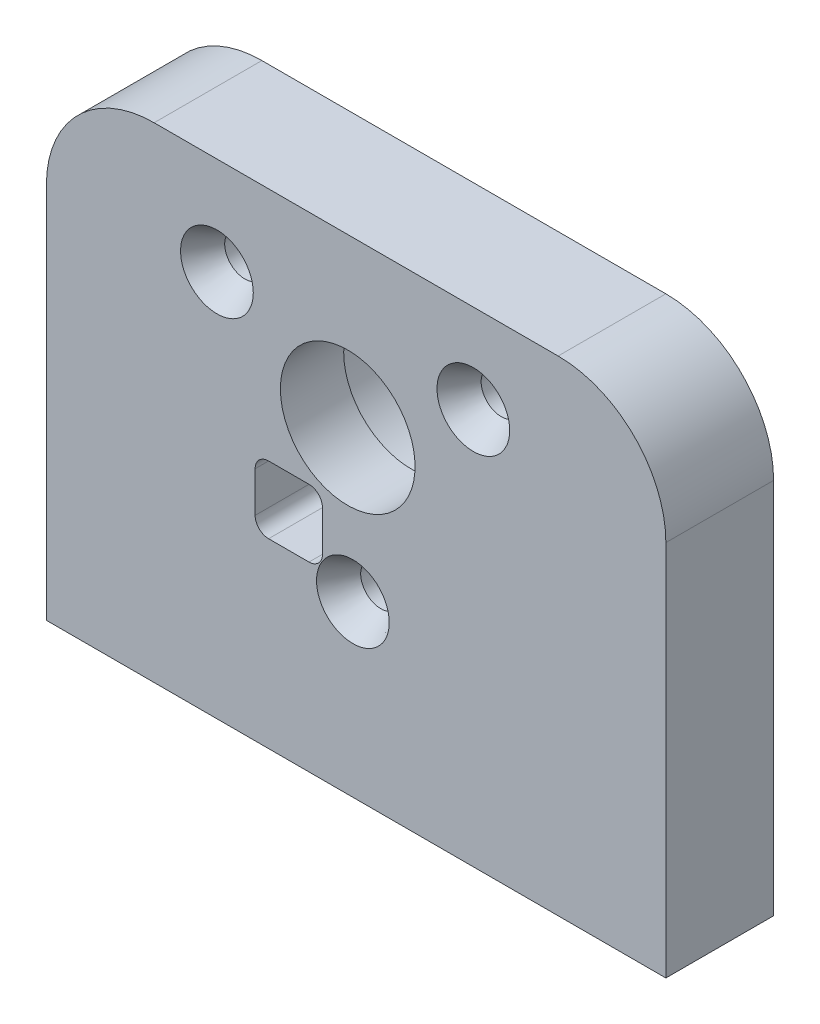
SolidWorks part; units mm, degrees
ref_plane "Front Plane" through (0, 0, 0) normal (0, 0, 1) x (1, 0, 0)
ref_plane "Top Plane" through (0, 0, 0) normal (0, 1, 0) x (1, 0, 0)
ref_plane "Right Plane" through (0, 0, 0) normal (1, 0, 0) x (0, 0, -1)
ref_plane "Plane1" through (0, 0, 4.5) normal (0, 0, 1) x (1, 0, 0)
sketch "Sketch1" plane through (0, 0, 4.5) normal (0, 0, 1) x (1, 0, 0)
  line L0 (-23, -18) -> (23, -18)
  line L1 (23, -18) -> (23, 18)
  line L2 (23, 18) -> (-23, 18)
  line L3 (-23, 18) -> (-23, -18)
extrude "Boss-Extrude1" add sketch "Sketch1" against normal blind 8
hole_wizard "M3x0.5 Tapped Hole1" positions "Sketch6" profile "Sketch5" tap size "M3x0.5" standard "ANSI Metric"
sketch "Sketch6" plane through (0, -18, 0) normal (0, -1, 0) x (-1, 0, 0)
  line L0 (23, -4.5) -> (-23, -4.5) construction
  point P0 (0, -0.5)
  dimension "D1" = 4
sketch "Sketch5" plane through (0, -18, 0.5) normal (1, 0, 0) x (0, 0, -1)
  line L0 (0, 0) -> (0, 8.2511)
  line L1 (0, 8.2511) -> (1.25, 7.5)
  line L2 (1.25, 7.5) -> (1.25, 0)
  line L5 (1.25, 0) -> (0, 0)
  line L10 (0, 8.2511) -> (-1.25, 7.5) construction
  line L11 (0, -6.35) -> (0, 107.95) construction
  dimension "Tap Drill Dia." = 2.5
  dimension "Tap Drill Depth" = 7.5
  dimension "Drill Angle" = 118
hole_wizard "M3x0.5 Tapped Hole2" positions "Sketch8" profile "Sketch7" tap size "M3x0.5" standard "ANSI Metric"
sketch "Sketch8" plane through (0, -18, 0) normal (0, -1, 0) x (-1, 0, 0)
  point P0 (-19, -0.5)
  point P1 (19, -0.5)
sketch "Sketch7" plane through (19, -18, 0.5) normal (1, 0, 0) x (0, 0, -1)
  line L0 (0, 0) -> (0, 8.2511)
  line L1 (0, 8.2511) -> (1.25, 7.5)
  line L2 (1.25, 7.5) -> (1.25, 0)
  line L5 (1.25, 0) -> (0, 0)
  line L10 (0, 8.2511) -> (-1.25, 7.5) construction
  line L11 (0, -6.35) -> (0, 107.95) construction
  dimension "Tap Drill Dia." = 2.5
  dimension "Tap Drill Depth" = 7.5
  dimension "Drill Angle" = 118
fillet "Fillet2" radius 8 2 edges at (-23, 18, 0.5) (23, 18, 0.5)
sketch "Sketch13" plane through (0, 0, 4.5) normal (0, 0, 1) x (1, 0, 0)
  line L0 (-23, -18) -> (23, -18) construction
  line L1 (-7.5, -4.5) -> (-2.5, -4.5)
  line L2 (-7.5, -4.5) -> (-7.5, 0.5)
  line L3 (-7.5, 0.5) -> (-2.5, 0.5)
  line L4 (-2.5, -4.5) -> (-2.5, 0.5)
  line L5 (-7.5, -4.5) -> (-2.5, 0.5) construction
  line L6 (-7.5, 0.5) -> (-2.5, -4.5) construction
  line L7 (-23, 10) -> (-23, -18) construction
  point P0 (-5, -2)
  dimension "D1" = 16
  dimension "D2" = 18
  dimension "D3" = 5
extrude "Cut-Extrude1" cut sketch "Sketch13" against normal blind 4.5
hole_wizard "CSK for M3 SFHCS1" positions "3DSketch1" profile "Sketch14" countersink size "M3" standard "ANSI Metric"
sketch3d "3DSketch1"
  line L0 (-23, 10, -3.5) -> (-23, -18, -3.5) construction
  line L1 (-23, -18, -3.5) -> (23, -18, -3.5) construction
  point P0 (-5, -2, -3.5)
  dimension "D1" = 18
  dimension "D2" = 16
sketch "Sketch14" plane through (-5, -2, -3.5) normal (1, 0, 0) x (0, 1, 0)
  line L0 (0, 0) -> (0, 10.4013)
  line L1 (0, 10.4013) -> (1.5, 9.5)
  line L2 (1.5, 9.5) -> (1.5, 1.9919)
  line L3 (1.5, 1.9919) -> (2.65, 0)
  line L5 (2.65, 0) -> (0, 0)
  line L6 (-1.5, 1.9919) -> (-2.65, 0) construction
  line L10 (0, 10.4013) -> (-1.5, 9.5) construction
  line L11 (0, -6.35) -> (0, 107.95) construction
  dimension "Hole Dia." = 3
  dimension "Hole Depth" = 9.5
  dimension "Near C'Sink Dia." = 5.3
  dimension "Near C'Sink Angle" = 60
  dimension "Drill Angle" = 118
fillet "Fillet3" radius 1 4 edges at (-7.5, -4.5, 2.25) (-2.5, -4.5, 2.25) (-2.5, 0.5, 2.25) (-7.5, 0.5, 2.25)
hole_wizard "Hole1" positions "Sketch10" profile "Sketch9" legacy end condition through all
sketch "Sketch10" plane through (0, 0, -3.5) normal (0, 0, -1) x (-1, 0, 0)
  line L0 (5, -2) -> (0.625, 5.5777) construction
  line L5 (0.625, 5.5777) -> (0.625, -18) construction
  line L6 (23, -18) -> (-23, -18) construction
  point P0 (0.625, 5.5777)
  dimension "D1" = 8.75
  dimension "D2" = 30
sketch "Sketch9" plane through (-0.625, 5.5777, -3.5) normal (1, 0, 0) x (0, 1, 0)
  line L0 (0, 0) -> (0, 8)
  line L1 (0, 8) -> (5, 8)
  line L2 (5, 8) -> (5, 3.3)
  line L3 (5, 3.3) -> (6, 3.3)
  line L4 (6, 3.3) -> (6, 0)
  line L5 (6, 0) -> (0, 0)
  line L6 (0, 110) -> (0, -10) construction
  dimension "Diameter" = 10
  dimension "Depth" = 8
  dimension "C-Bore Diameter" = 12
  dimension "C-Bore Depth" = 3.3
hole_wizard "CSK for M3 SFHCS2" positions "Sketch12" profile "Sketch11" countersink size "M3" standard "ANSI Metric"
sketch "Sketch12" plane through (0, 0, 4.5) normal (0, 0, 1) x (1, 0, 0)
  line L1 (8.7035, 11.4068) -> (-10.3374, 10.7419) construction
  line L2 (-10.3374, 10.7419) -> (-0.2411, -5.4156) construction
  line L3 (-0.2411, -5.4156) -> (8.7035, 11.4068) construction
  line L4 (-0.625, 18) -> (-0.625, -18) construction
  line L5 (15, 18) -> (-15, 18) construction
  line L6 (-23, -18) -> (23, -18) construction
  line L9 (-0.625, 5.5777) -> (-0.2411, -5.4156) construction
  circle A0 centre (-0.625, 5.5777) radius 5.5 construction
  point P31 (-10.3374, 10.7419)
  point P34 (8.7035, 11.4068)
  point P43 (-0.2411, -5.4156)
  dimension "D1" = 2
sketch "Sketch11" plane through (-10.3374, 10.7419, 4.5) normal (1, 0, 0) x (0, -1, 0)
  line L0 (0, 0) -> (0, 10.4013)
  line L1 (0, 10.4013) -> (1.5, 9.5)
  line L2 (1.5, 9.5) -> (1.5, 2.0785)
  line L3 (1.5, 2.0785) -> (2.7, 0)
  line L5 (2.7, 0) -> (0, 0)
  line L6 (-1.5, 2.0785) -> (-2.7, 0) construction
  line L10 (0, 10.4013) -> (-1.5, 9.5) construction
  line L11 (0, -6.35) -> (0, 107.95) construction
  dimension "Hole Dia." = 3
  dimension "Hole Depth" = 9.5
  dimension "Near C'Sink Dia." = 5.4
  dimension "Near C'Sink Angle" = 60
  dimension "Drill Angle" = 118
